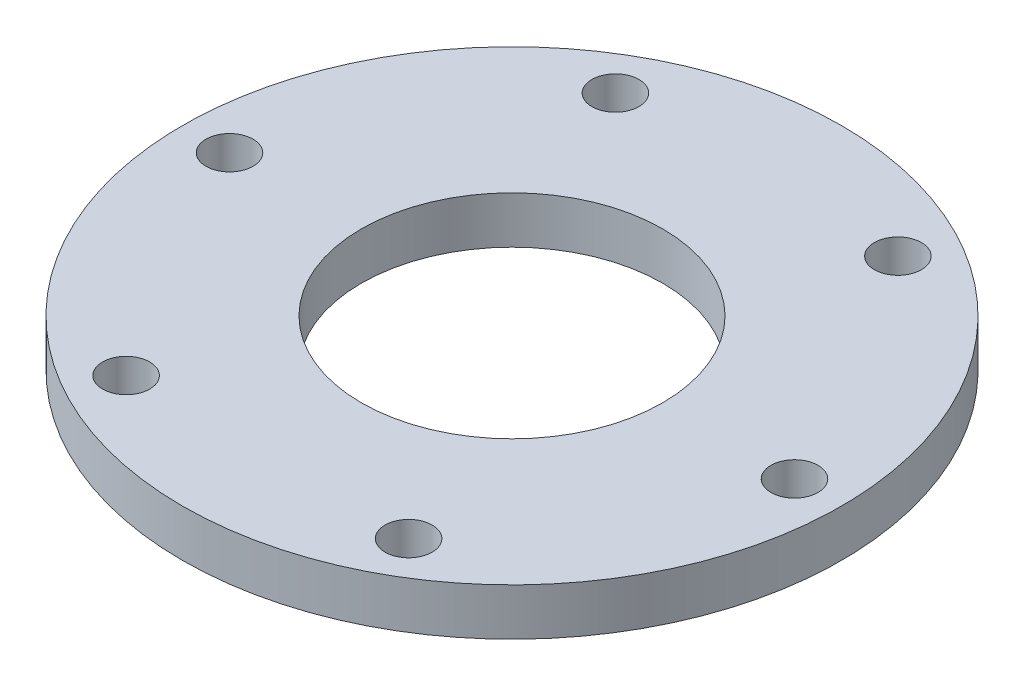
SolidWorks part; units mm, degrees
ref_plane "Front Plane" through (0, 0, 0) normal (0, 0, 1) x (1, 0, 0)
ref_plane "Top Plane" through (0, 0, 0) normal (0, 1, 0) x (1, 0, 0)
ref_plane "Right Plane" through (0, 0, 0) normal (1, 0, 0) x (0, 0, -1)
sketch "Sketch2" plane through (0, 0, 0) normal (0, 1, 0) x (1, 0, 0)
  line L0 (0, 0) -> (38.1, 0) construction
  circle A0 centre (0, 0) radius 44.45
  circle A1 centre (0, 0) radius 20.32
  circle A2 centre (38.1, 0) radius 3.175
  circle A3 centre (19.05, -32.9956) radius 3.175
  circle A4 centre (-19.05, -32.9956) radius 3.175
  circle A5 centre (-38.1, 0) radius 3.175
  circle A6 centre (-19.05, 32.9956) radius 3.175
  circle A7 centre (19.05, 32.9956) radius 3.175
  point P6 (0, 0)
  point P19 (0, 0)
  dimension "D1" = 88.9
  dimension "D2" = 40.64
  dimension "D3" = 6.35
  dimension "D4" = 38.1
  dimension "D5" = 6
extrude "Boss-Extrude1" add sketch "Sketch2" along normal blind 6.35
